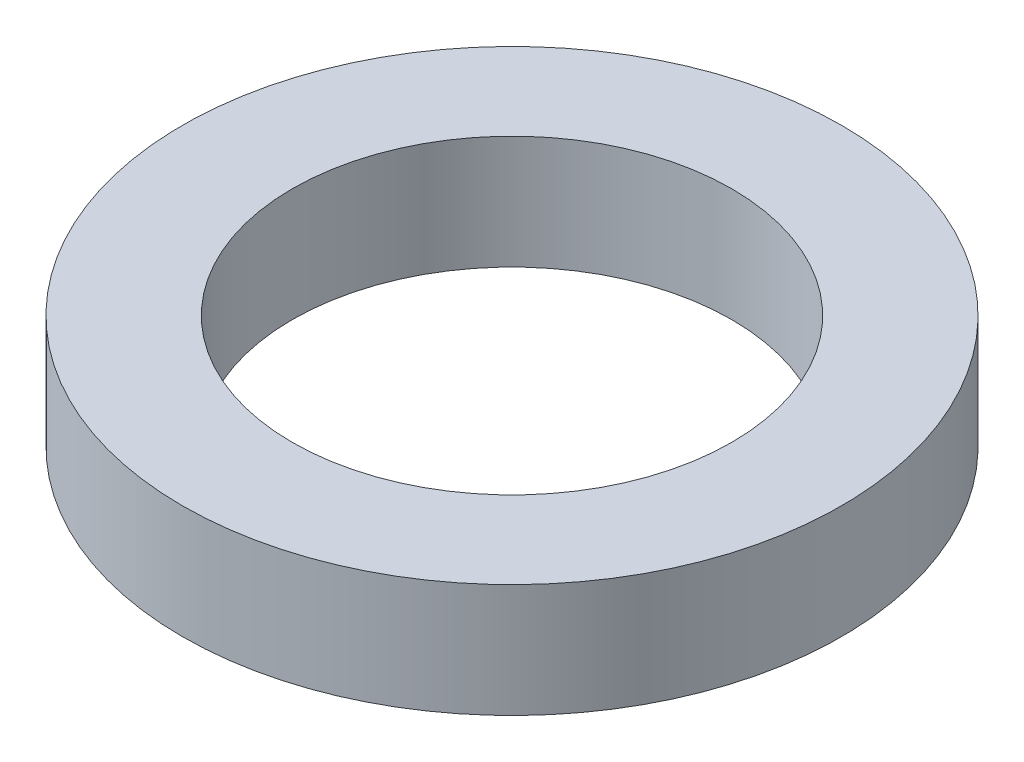
SolidWorks part; units mm, degrees
ref_plane "Front Plane" through (0, 0, 0) normal (0, 0, 1) x (1, 0, 0)
ref_plane "Top Plane" through (0, 0, 0) normal (0, 1, 0) x (1, 0, 0)
ref_plane "Right Plane" through (0, 0, 0) normal (1, 0, 0) x (0, 0, -1)
sketch "Sketch1" plane through (0, 0, 0) normal (0, 1, 0) x (1, 0, 0)
  circle A0 centre (0, 0) radius 3.175
  dimension "D1" = 6.35
extrude "Extrude-Thin1" add sketch "Sketch1" along normal blind 1.6383 thin
